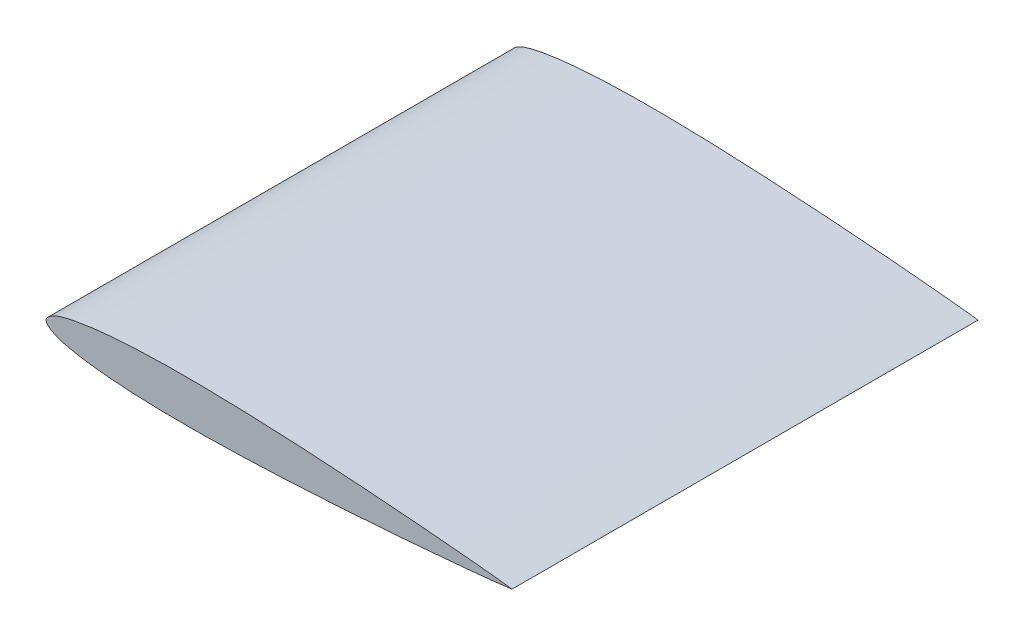
SolidWorks part; units mm, degrees
ref_plane "Front Plane" through (0, 0, 0) normal (0, 0, 1) x (1, 0, 0)
ref_plane "Top Plane" through (0, 0, 0) normal (0, 1, 0) x (1, 0, 0)
ref_plane "Right Plane" through (0, 0, 0) normal (1, 0, 0) x (0, 0, -1)
curve "Curve1"
  spline degree 3 poles (990.8652, -0.9511, 0) (1002.2959, 0, 0) (990.8652, 0.9511, 0) (981.4966, 2.5372, 0) (958.7395, 4.9688, 0) (930.7792, 7.9871, 0) (894.3471, 11.5291, 0) (851.5737, 15.4379, 0) (802.6464, 19.638, 0) (748.5888, 24.0066, 0) (690.2628, 28.3691, 0) (628.6855, 32.5963, 0) (564.9061, 36.4936, 0) (500.0164, 39.8961, 0) (435.1246, 42.6014, 0) (381.5433, 44.1643, 0) (339.5117, 44.8822, 0) (308.9339, 45.137, 0) (279.1721, 45.1014, 0) (250.3536, 44.7183, 0) (222.6042, 44.0458, 0) (196.0449, 43.0302, 0) (170.7873, 41.7085, 0) (146.9363, 40.0498, 0) (124.593, 38.0822, 0) (103.8602, 35.7885, 0) (84.8245, 33.2124, 0) (67.5602, 30.4204, 0) (52.1393, 27.4249, 0) (38.6118, 24.2363, 0) (27.0418, 20.7473, 0) (17.4544, 16.8931, 0) (9.9374, 12.6406, 0) (4.5317, 8.2, 0) (1.1558, 4.1301, 0) (-0.473, 0, 0) (1.1558, -4.1301, 0) (4.5317, -8.2, 0) (9.9374, -12.6406, 0) (17.4544, -16.8931, 0) (27.0418, -20.7473, 0) (38.6118, -24.2363, 0) (52.1393, -27.4249, 0) (67.5602, -30.4204, 0) (84.8245, -33.2124, 0) (103.8602, -35.7885, 0) (124.593, -38.0822, 0) (146.9363, -40.0498, 0) (170.7873, -41.7085, 0) (196.0449, -43.0302, 0) (222.6042, -44.0458, 0) (250.3536, -44.7183, 0) (279.1721, -45.1014, 0) (308.9339, -45.137, 0) (339.5117, -44.8822, 0) (381.5433, -44.1643, 0) (435.1246, -42.6014, 0) (500.0164, -39.8961, 0) (564.9061, -36.4936, 0) (628.6855, -32.5963, 0) (690.2628, -28.3691, 0) (748.5888, -24.0066, 0) (802.6464, -19.638, 0) (851.5737, -15.4379, 0) (894.3471, -11.5291, 0) (930.7792, -7.9871, 0) (958.7395, -4.9688, 0) (981.4966, -2.5372, 0) (990.8652, -0.9511, 0) (1002.2959, 0, 0) (990.8652, 0.9511, 0) knots -0.018944 -0.008488 -0.002133 0 0.002133 0.008488 0.018944 0.033319 0.051356 0.072756 0.097141 0.124097 0.153163 0.183834 0.215589 0.247878 0.280151 0.31186 0.327333 0.342463 0.357187 0.371448 0.385183 0.398331 0.410845 0.422673 0.433769 0.44409 0.453589 0.46224 0.47001 0.476871 0.482833 0.487909 0.492155 0.495592 0.498196 0.5 0.501804 0.504408 0.507845 0.512091 0.517167 0.523129 0.52999 0.53776 0.546411 0.55591 0.566231 0.577327 0.589155 0.601669 0.614817 0.628552 0.642813 0.657537 0.672667 0.68814 0.719849 0.752122 0.784411 0.816166 0.846837 0.875903 0.902859 0.927244 0.948644 0.966681 0.981056 0.991512 0.997867 1 1.002133 1.008488 1.018944 periodic
sketch "Sketch1" plane through (0, 0, 0) normal (0, 0, 1) x (1, 0, 0)
  line L0 (-26.8156, 0.0291) -> (-26.8156, 25.4446) construction
  line L1 (-26.8156, 0.0291) -> (-26.7055, 22.046) construction
  line L2 (-26.8142, -0.0098) -> (73.1858, 0.0269) construction
  line L3 (0, 4.5207) -> (0, -4.467) construction
  spline S2 degree 3 poles (72.2724, -0.0683) (73.4154, 0.0269) (72.2724, 0.122) (71.3355, 0.2806) (69.0597, 0.5237) (66.2637, 0.8256) (62.6204, 1.1798) (58.343, 1.5707) (53.4502, 1.9907) (48.0444, 2.4275) (42.2117, 2.8638) (36.0539, 3.2865) (29.6758, 3.6763) (23.1868, 4.0165) (16.6975, 4.2871) (11.3393, 4.4433) (7.1361, 4.5151) (4.0782, 4.5406) (1.102, 4.5371) (-1.7799, 4.4988) (-4.5549, 4.4315) (-7.2108, 4.3299) (-9.7366, 4.1978) (-12.1218, 4.0319) (-14.3561, 3.8351) (-16.4294, 3.6058) (-18.333, 3.3481) (-20.0595, 3.0689) (-21.6016, 2.7694) (-22.9544, 2.4505) (-24.1114, 2.1016) (-25.0701, 1.7162) (-25.8218, 1.2909) (-26.3624, 0.8469) (-26.7, 0.4399) (-26.8629, 0.0269) (-26.7, -0.3862) (-26.3624, -0.7932) (-25.8218, -1.2372) (-25.0701, -1.6625) (-24.1114, -2.0479) (-22.9544, -2.3968) (-21.6016, -2.7157) (-20.0595, -3.0152) (-18.333, -3.2944) (-16.4294, -3.552) (-14.3561, -3.7814) (-12.1218, -3.9782) (-9.7366, -4.144) (-7.2108, -4.2762) (-4.5549, -4.3778) (-1.7799, -4.445) (1.102, -4.4833) (4.0782, -4.4869) (7.1361, -4.4614) (11.3393, -4.3896) (16.6975, -4.2333) (23.1868, -3.9628) (29.6758, -3.6226) (36.0539, -3.2328) (42.2117, -2.8101) (48.0444, -2.3738) (53.4502, -1.937) (58.343, -1.517) (62.6204, -1.1261) (66.2637, -0.7719) (69.0597, -0.47) (71.3355, -0.2269) (72.2724, -0.0683) (73.4154, 0.0269) (72.2724, 0.122) knots -0.018944 -0.008488 -0.002133 0 0.002133 0.008488 0.018944 0.033319 0.051356 0.072756 0.097141 0.124097 0.153163 0.183834 0.215589 0.247878 0.280151 0.31186 0.327333 0.342463 0.357187 0.371448 0.385183 0.398331 0.410845 0.422673 0.433769 0.44409 0.453589 0.46224 0.47001 0.476871 0.482833 0.487909 0.492155 0.495592 0.498196 0.5 0.501804 0.504408 0.507845 0.512091 0.517167 0.523129 0.52999 0.53776 0.546411 0.55591 0.566231 0.577327 0.589155 0.601669 0.614817 0.628552 0.642813 0.657537 0.672667 0.68814 0.719849 0.752122 0.784411 0.816166 0.846837 0.875903 0.902859 0.927244 0.948644 0.966681 0.981056 0.991512 0.997867 1 1.002133 1.008488 1.018944 only from (73.1858, 0.0269) to (73.1858, 0.0269)
  dimension "D1" = 100
extrude "Boss-Extrude1" add sketch "Sketch1" along normal blind 100
